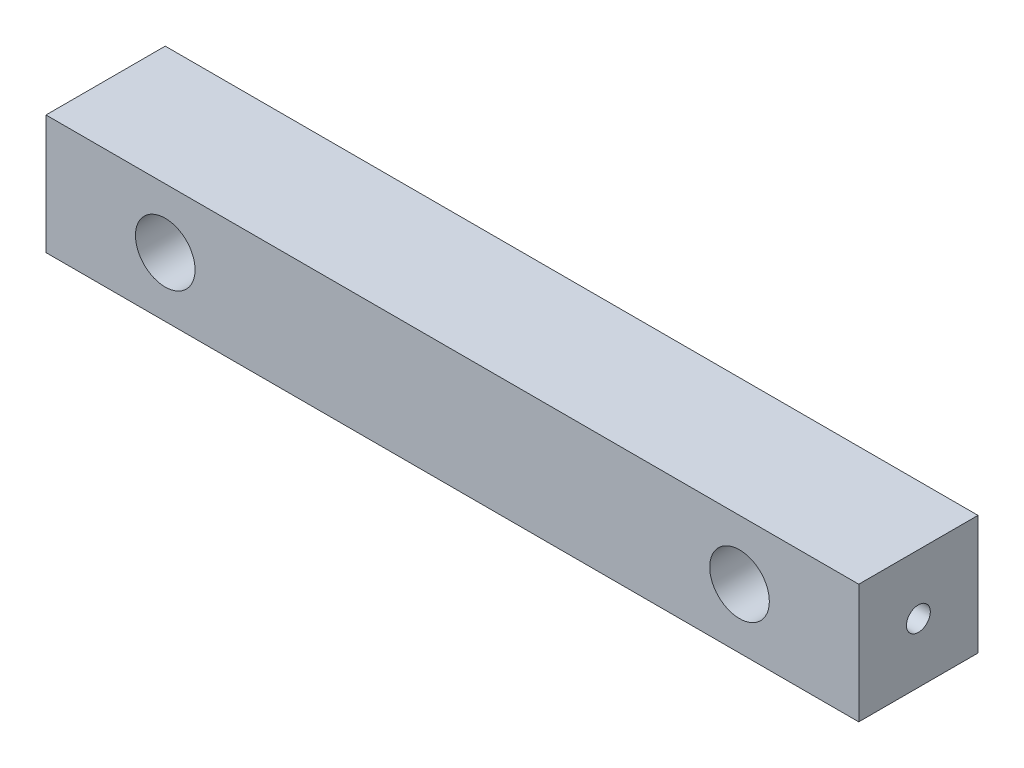
SolidWorks part; units mm, degrees
material "1060 Alloy"
ref_plane "Front Plane" through (0, 0, 0) normal (0, 0, 1) x (1, 0, 0)
ref_plane "Top Plane" through (0, 0, 0) normal (0, 1, 0) x (1, 0, 0)
ref_plane "Right Plane" through (0, 0, 0) normal (1, 0, 0) x (0, 0, -1)
sketch "Sketch1" plane through (0, 0, 0) normal (0, 0, 1) x (1, 0, 0)
  line L1 (0, 0) -> (136.32, 0)
  line L2 (0, 0) -> (0, 20)
  line L3 (0, 20) -> (136.32, 20)
  line L4 (136.32, 0) -> (136.32, 20)
  circle A0 centre (116.32, 10) radius 5
  circle A1 centre (20, 10) radius 5
  point P9 (0, 10)
  point P10 (136.32, 10)
  dimension "D3" = 10
  dimension "D4" = 10
  dimension "D1" = 136.32
  dimension "D2" = 20
  dimension "D5" = 0
  dimension "D6" = 0
  dimension "D7" = 20
  dimension "D8" = 20
extrude "Boss-Extrude1" add sketch "Sketch1" along normal blind 20
sketch "Sketch2" plane through (0, 0, 0) normal (-1, 0, 0) x (0, 0, 1)
  line L0 (20, 0) -> (0, 0) construction
  line L1 (0, 20) -> (0, 0) construction
  circle A0 centre (10, 10) radius 2
  point P4 (10, 0)
  point P7 (0, 10)
  dimension "D1" = 4
  dimension "D2" = 10
  dimension "D3" = 10
extrude "Cut-Extrude1" cut sketch "Sketch2" against normal blind 7.5
sketch "Sketch3" plane through (136.32, 0, 0) normal (1, 0, 0) x (0, 0, -1)
  circle A0 centre (-10, 10) radius 2 construction
  circle A1 centre (-10, 10) radius 2
extrude "Cut-Extrude2" cut sketch "Sketch3" against normal blind 7.5
